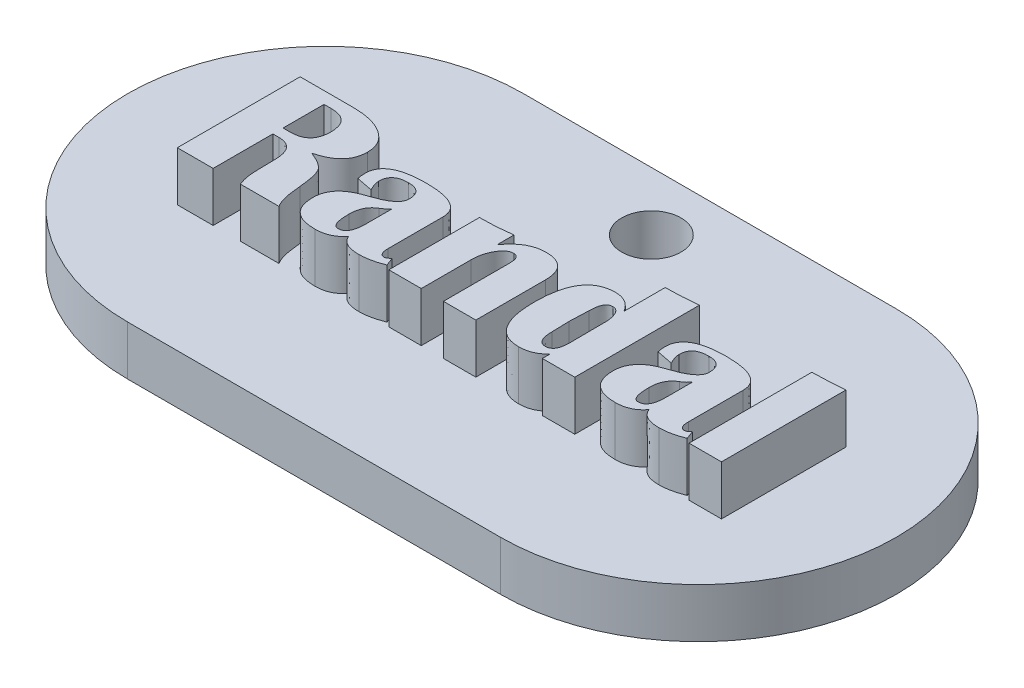
SolidWorks part; units mm, degrees
ref_plane "Front Plane" through (0, 0, 0) normal (0, 0, 1) x (1, 0, 0)
ref_plane "Top Plane" through (0, 0, 0) normal (0, 1, 0) x (1, 0, 0)
ref_plane "Right Plane" through (0, 0, 0) normal (1, 0, 0) x (0, 0, -1)
sketch "Sketch1" plane through (0, 0, 0) normal (0, 1, 0) x (1, 0, 0)
  line L0 (-9.4227, 0) -> (9.4227, 0) construction
  line L1 (-9.4227, 10) -> (9.4227, 10)
  line L2 (-9.4227, -10) -> (9.4227, -10)
  arc A0 (-9.4227, 10) -> (-9.4227, -10) centre (-9.4227, 0) ccw
  arc A1 (9.4227, -10) -> (9.4227, 10) centre (9.4227, 0) ccw
  point P3 (0, 0)
extrude "Boss-Extrude1" add sketch "Sketch1" along normal blind 2.5
sketch "Sketch2" plane through (0, 2.5, 0) normal (0, 1, 0) x (1, 0, 0)
  text T0 "Randal" font "Britannic Bold" height in points 26
extrude "Boss-Extrude2" add sketch "Sketch2" along normal blind 2.5
sketch "Sketch3" plane through (0, 2.5, 0) normal (0, 1, 0) x (1, 0, 0)
  circle A0 centre (0, 7.0417) radius 1.5
extrude "Cut-Extrude1" cut sketch "Sketch3" against normal blind 5
